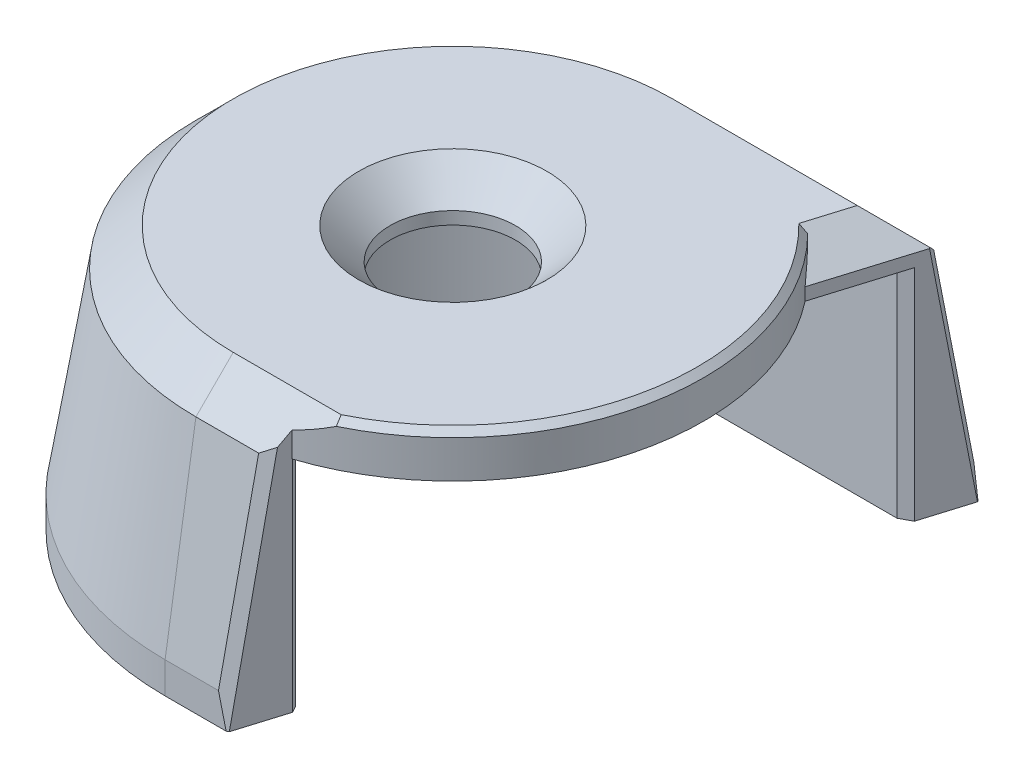
SolidWorks part; units mm, degrees
ref_plane "Front Plane" through (0, 0, 0) normal (0, 0, 1) x (1, 0, 0)
ref_plane "Top Plane" through (0, 0, 0) normal (0, 1, 0) x (1, 0, 0)
ref_plane "Right Plane" through (0, 0, 0) normal (1, 0, 0) x (0, 0, -1)
sketch "Sketch2" plane through (0, 0, 0) normal (1, 0, 0) x (0, 0, -1)
  line L0 (0, 0) -> (0, 39821.435) construction
  line L1 (37, 0) -> (45.85, 0)
  line L2 (45.85, 0) -> (45.85, 5)
  line L3 (45.85, 5) -> (40, 42)
  line L4 (40, 42) -> (0, 42)
  line L5 (0, 42) -> (0, 35)
  line L6 (0, 35) -> (37, 35)
  line L7 (37, 35) -> (37, 0)
  dimension "D1" = 91.7
  dimension "D2" = 35
  dimension "D3" = 7
  dimension "D4" = 74
  dimension "D5" = 3
  dimension "D6" = 5
revolve "Revolve1" add sketch "Sketch2" angle 180 about L0
sketch "Sketch7" plane through (0, 0, 0) normal (1, 0, 0) x (0, 0, -1)
  line L10 (-37, 0) -> (-37, 35)
  line L11 (-37, 35) -> (37, 35)
  line L12 (37, 35) -> (37, 0)
  line L13 (37, 0) -> (45.85, 0)
  line L14 (45.85, 0) -> (45.85, 5)
  line L15 (45.85, 5) -> (40, 42)
  line L16 (40, 42) -> (-40, 42)
  line L17 (-40, 42) -> (-45.85, 5)
  line L18 (-45.85, 5) -> (-45.85, 0)
  line L19 (-45.85, 0) -> (-37, 0)
  line L20 (-37, 0) -> (-37, 35)
  line L21 (-37, 35) -> (37, 35)
  line L22 (37, 35) -> (37, 0)
  line L23 (37, 0) -> (45.85, 0)
  line L24 (45.85, 0) -> (45.85, 5)
  line L25 (45.85, 5) -> (40, 42)
  line L26 (40, 42) -> (-40, 42)
  line L27 (-40, 42) -> (-45.85, 5)
  line L28 (-45.85, 5) -> (-45.85, 0)
  line L29 (-45.85, 0) -> (-37, 0)
  dimension "D1" = 0
extrude "Boss-Extrude1" add sketch "Sketch7" along normal blind 60
sketch "Sketch8" plane through (0, 0, 0) normal (0, 1, 0) x (1, 0, 0)
  line L0 (10, -45.85) -> (38, 45.85)
  line L1 (60, -45.85) -> (0, -45.85) construction
  line L2 (60, 45.85) -> (0, 45.85) construction
  line L3 (0, 0) -> (0, 26.5046) construction
  line L4 (38, 45.85) -> (138, 45.85)
  line L5 (138, 45.85) -> (138, -45.85)
  line L6 (138, -45.85) -> (10, -45.85)
  arc A0 (0, 45.85) -> (0, -45.85) centre (0, 0) ccw construction
  arc A1 (0, 45.85) -> (0, -45.85) centre (0, 0) ccw construction
  circle A2 centre (0, 0) radius 10
  dimension "D4" = 20
  dimension "D1" = 38
  dimension "D2" = 10
  dimension "D3" = 100
extrude "Cut-Extrude2" cut sketch "Sketch8" against normal through all both and the other way through all
sketch "Sketch9" plane through (0, 42, 0) normal (0, 1, 0) x (1, 0, 0)
  line L0 (36.2137, 40) -> (11.7863, -40) construction
  line L1 (31.5198, 24.6273) -> (0, -40)
  arc A0 (0, -40) -> (31.5198, 24.6273) centre (0, 0) ccw
extrude "Boss-Extrude2" add sketch "Sketch9" against normal up to surface (7 mm away)
chamfer "Chamfer1" distance 5 angle 45 5 edges at (5.8931, 42, 40) (18.1069, 42, -40) (0, 42, 10) (33.8668, 42, -32.3136) (12.0864, 42, 39.0169)
chamfer "Chamfer2" distance 1 angle 45 5 edges at (39.6716, 42, 5.1152) (12.7023, 17.5, 37) (35.2977, 17.5, -37) (37.2502, 20.5305, -43.3945) (10.7498, 20.5305, 43.3945)
